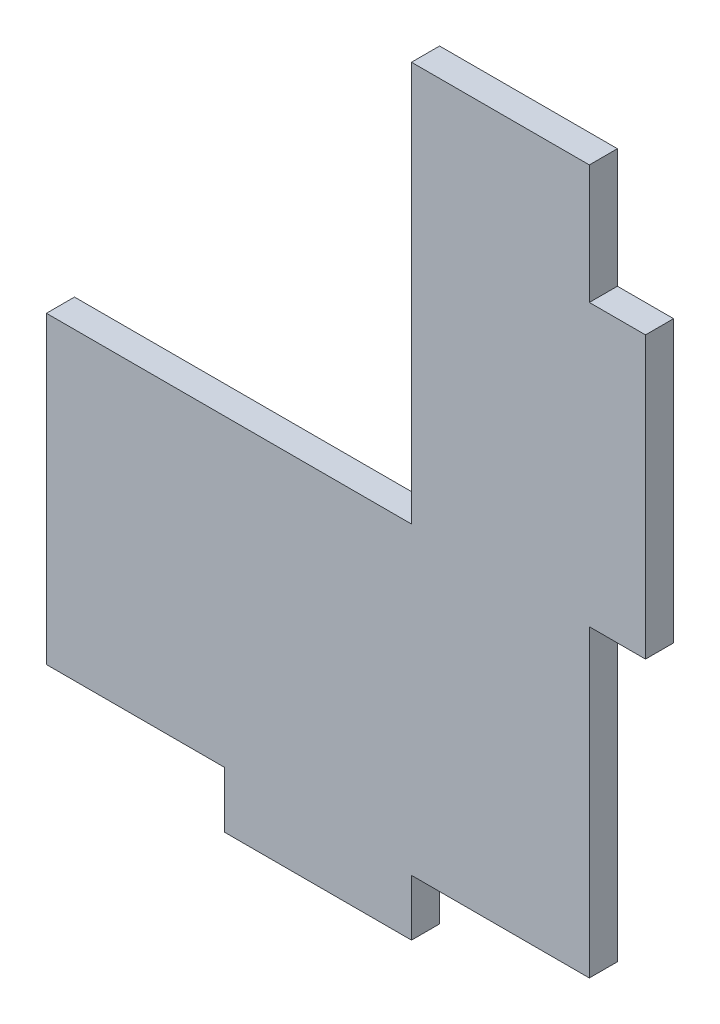
SolidWorks part; units mm, degrees
ref_plane "Plan de face" through (0, 0, 0) normal (0, 0, 1) x (1, 0, 0)
ref_plane "Plan de dessus" through (0, 0, 0) normal (0, 1, 0) x (1, 0, 0)
ref_plane "Plan de droite" through (0, 0, 0) normal (1, 0, 0) x (0, 0, -1)
sketch "Esquisse1" plane through (0, 0, 0) normal (0, 0, 1) x (1, 0, 0)
  line L1 (0, 0) -> (-70, 0)
  line L2 (0, 0) -> (0, 110)
  line L3 (0, 110) -> (-70, 110)
  line L4 (-70, 0) -> (-70, 110)
  dimension "D1" = 110
  dimension "D2" = 70
extrude "Boss.-Extru.1" add sketch "Esquisse1" along normal blind 3
sketch "Esquisse2" plane through (0, 0, 0) normal (0, 0, -1) x (-1, 0, 0)
  line L0 (0, 110) -> (70, 110) construction
  line L1 (0, 110) -> (25, 110)
  line L2 (0, 110) -> (0, 68.5)
  line L3 (6, 104) -> (25, 104)
  line L4 (25, 110) -> (25, 104)
  line L5 (70, 110) -> (45, 110)
  line L6 (0, 0) -> (25, 0)
  line L7 (64, 104) -> (45, 104)
  line L8 (45, 110) -> (45, 104)
  line L9 (70, 110) -> (70, 0) construction
  line L10 (45, 0) -> (70, 0)
  line L11 (70, 110) -> (70, 68.5)
  line L12 (70, 0) -> (70, 38.5)
  line L13 (0, 68.5) -> (6, 68.5)
  line L14 (6, 104) -> (6, 68.5)
  line L16 (0, 0) -> (0, 38.5)
  line L17 (0, 38.5) -> (6, 38.5)
  line L18 (6, 6) -> (6, 38.5)
  line L21 (6, 6) -> (25, 6)
  line L22 (25, 0) -> (25, 6)
  line L25 (64, 6) -> (45, 6)
  line L26 (45, 0) -> (45, 6)
  line L29 (70, 38.5) -> (64, 38.5)
  line L30 (64, 6) -> (64, 38.5)
  line L33 (70, 68.5) -> (64, 68.5)
  line L34 (64, 104) -> (64, 68.5)
  dimension "D1" = 6
  dimension "D2" = 20
  dimension "D3" = 6
  dimension "D4" = 25
  dimension "D5" = 6
  dimension "D6" = 30
  dimension "D7" = 41.5
  dimension "D8" = 6
  dimension "D9" = 6
  dimension "D10" = 6
  dimension "D11" = 41.5
  dimension "D12" = 19
  dimension "D13" = 20
  dimension "D14" = 6
  dimension "D15" = 30
  dimension "D16" = 6
extrude "Enlèv. mat.-Extru.1" cut sketch "Esquisse2" against normal through all
sketch "Esquisse3" plane through (0, 0, 3) normal (0, 0, 1) x (1, 0, 0)
  line L1 (-70, 38.5) -> (-25, 38.5)
  line L2 (-70, 38.5) -> (-70, 110)
  line L3 (-70, 110) -> (-25, 110)
  line L4 (-25, 38.5) -> (-25, 81.2257)
  line L5 (-25, 81.2257) -> (-2.2359, 81.2257)
  line L7 (-25, 110) -> (-2.2359, 110)
  line L8 (-2.2359, 81.2257) -> (-2.2359, 110)
extrude "Enlèv. mat.-Extru.2" cut sketch "Esquisse3" against normal blind 10
